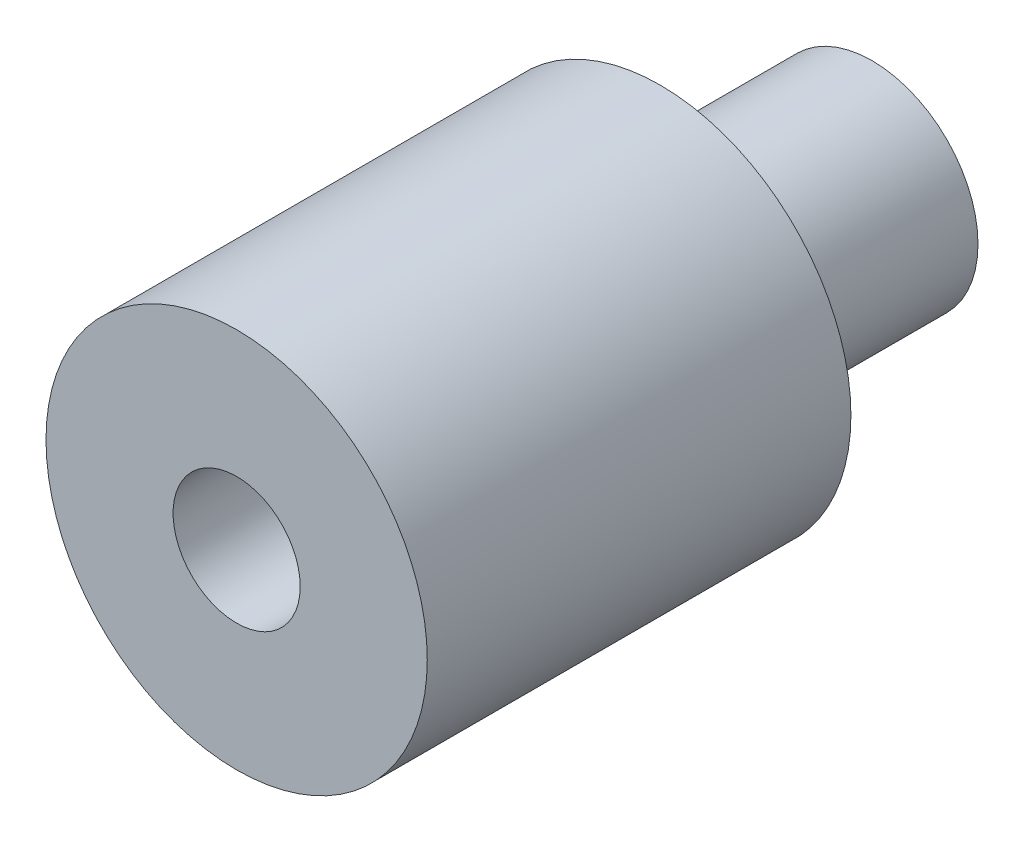
SolidWorks part; units mm, degrees
material "ABS"
ref_plane "X-Y Datum" through (0, 0, 0) normal (0, 0, 1) x (1, 0, 0)
ref_plane "X-Z Datum" through (0, 0, 0) normal (0, 1, 0) x (1, 0, 0)
ref_plane "Y-Z Datum" through (0, 0, 0) normal (1, 0, 0) x (0, 0, -1)
sketch "Sketch1" plane through (0, 0, 0) normal (0, 0, 1) x (1, 0, 0)
  circle A0 centre (0, 0) radius 2.5
  dimension "D1" = 5
extrude "Boss-Extrude1" add sketch "Sketch1" along normal blind 5
sketch "Sketch2" plane through (0, 0, 5) normal (0, 0, 1) x (1, 0, 0)
  circle A0 centre (0, 0) radius 4.5
  circle A1 centre (0, 0) radius 1.5 construction
  dimension "D1" = 3
  dimension "D2" = 9
extrude "Boss-Extrude2" add sketch "Sketch2" along normal blind 10 contours A0
sketch "Sketch3" plane through (0, 0, 15) normal (0, 0, 1) x (1, 0, 0)
  circle A0 centre (0, 0) radius 1.5
  dimension "D1" = 3
extrude "Cut-Extrude1" cut sketch "Sketch3" against normal blind 8
